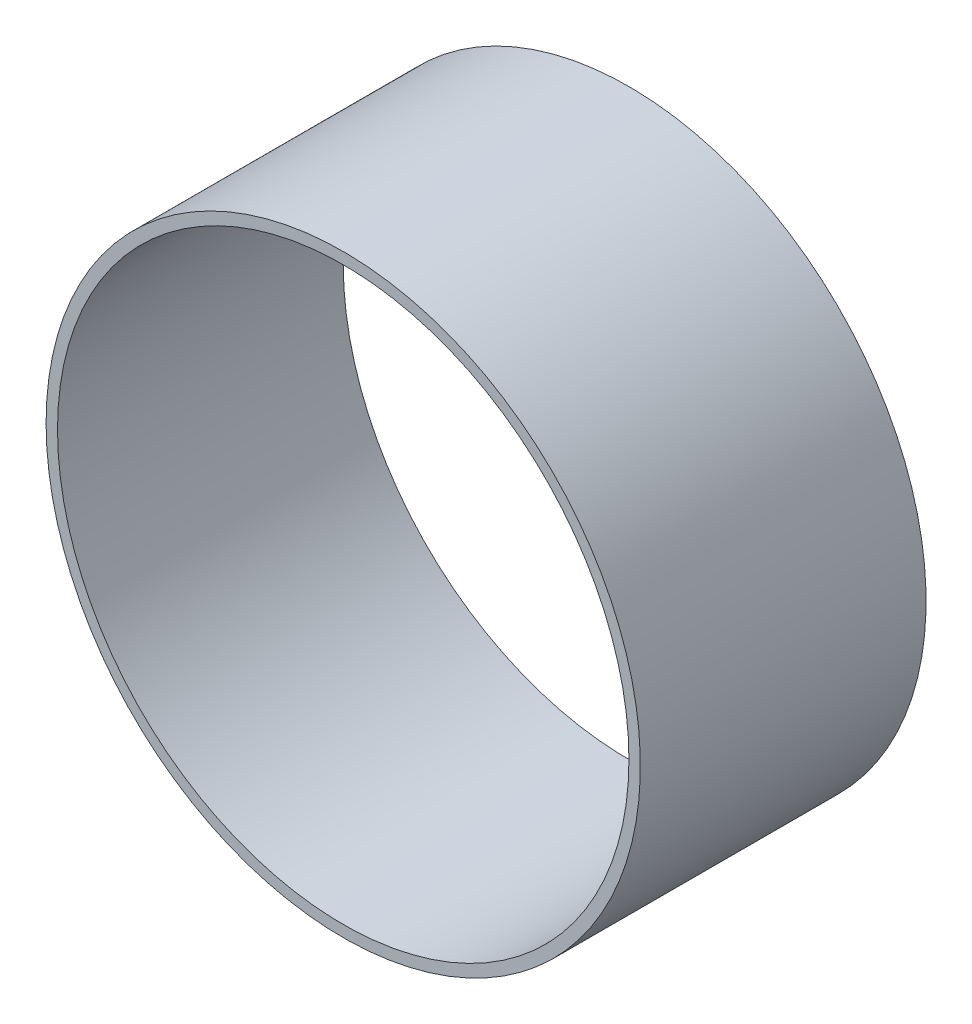
SolidWorks part; units mm, degrees
ref_plane "Front Plane" through (0, 0, 0) normal (0, 0, 1) x (1, 0, 0)
ref_plane "Top Plane" through (0, 0, 0) normal (0, 1, 0) x (1, 0, 0)
ref_plane "Right Plane" through (0, 0, 0) normal (1, 0, 0) x (0, 0, -1)
sketch "Sketch1" plane through (0, 0, 0) normal (0, 0, 1) x (1, 0, 0)
  circle A0 centre (0, 0) radius 39.624
  circle A1 centre (0, 0) radius 38.1
  dimension "D1" = 79.248
  dimension "D2" = 76.2
extrude "Boss-Extrude1" add sketch "Sketch1" along normal blind 38.1
